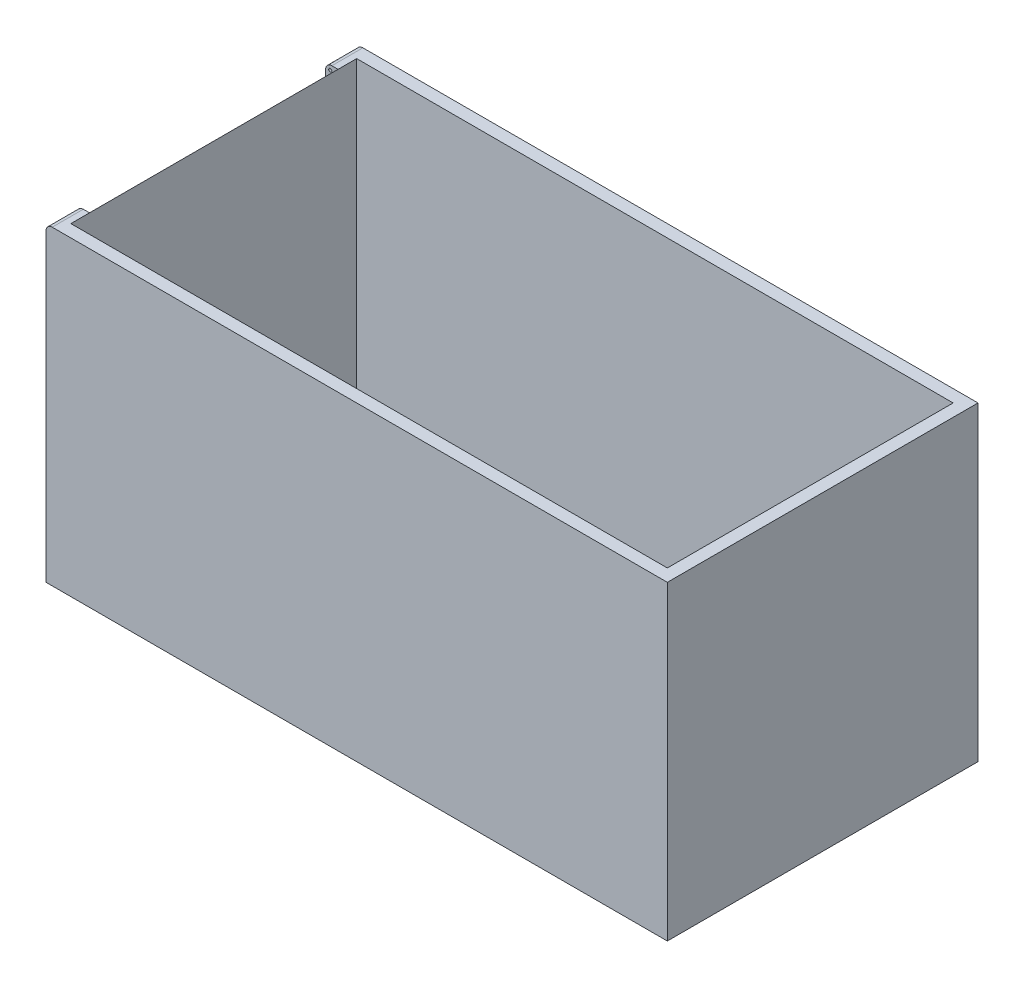
SolidWorks part; units mm, degrees
ref_plane "Front Plane" through (0, 0, 0) normal (0, 0, 1) x (1, 0, 0)
ref_plane "Top Plane" through (0, 0, 0) normal (0, 1, 0) x (1, 0, 0)
ref_plane "Right Plane" through (0, 0, 0) normal (1, 0, 0) x (0, 0, -1)
sketch "Sketch2" plane through (0, 0, 0) normal (0, 1, 0) x (1, 0, 0)
  line L1 (-63.5, -31.75) -> (63.5, -31.75)
  line L2 (-63.5, -31.75) -> (-63.5, 31.75)
  line L3 (-63.5, 31.75) -> (63.5, 31.75)
  line L4 (63.5, -31.75) -> (63.5, 31.75)
  line L5 (-63.5, -31.75) -> (63.5, 31.75) construction
  line L6 (-63.5, 31.75) -> (63.5, -31.75) construction
  point P0 (0, 0)
  dimension "D1" = 127
  dimension "D2" = 63.5
extrude "Boss-Extrude1" add sketch "Sketch2" along normal blind 63.5
shell "Shell1" thickness 2.54
sketch "Sketch4" plane through (0, 0, 0) normal (0, 0, 1) x (1, 0, 0)
  line L0 (-60.96, 63.5) -> (-63.5, 63.5)
  line L1 (-63.5, 63.5) -> (-63.5, 60.96)
  arc A0 (-63.5, 60.96) -> (-60.96, 63.5) centre (-63.5, 63.5) ccw
  point P3 (0, 0)
  dimension "D1" = 2.54
extrude "Cut-Extrude1" cut sketch "Sketch4" against normal blind 25.4 and the other way blind 25.4
sketch "Sketch5" plane through (0, 0, -25.4) normal (0, 0, 1) x (1, 0, 0)
  line L6 (-63.5, 63.5) -> (63.5, 63.5) construction
  line L7 (-62.23, 63.5) -> (-62.23, 62.23)
  line L8 (-62.23, 62.23) -> (-63.5, 62.23)
  line L9 (-63.5, 63.5) -> (-63.5, 0) construction
  line L10 (-62.23, 62.865) -> (-62.865, 62.865)
  line L11 (-62.865, 62.865) -> (-62.865, 62.23)
  circle A1 centre (-62.5475, 62.5475) radius 0.3175
  line M5 (-63.5, 63.5) -> (-63.5, 60.96)
  dimension "D1" = 1.27
  dimension "D2" = 1.27
extrude "Cut-Extrude2" cut sketch "Sketch5" against normal blind 1.27 and the other way blind 52.07 contours A1 M5
fillet "Fillet1" radius 1.27 2 edges at (-63.5, 63.5, 28.575) (-63.5, 63.5, -28.575)
